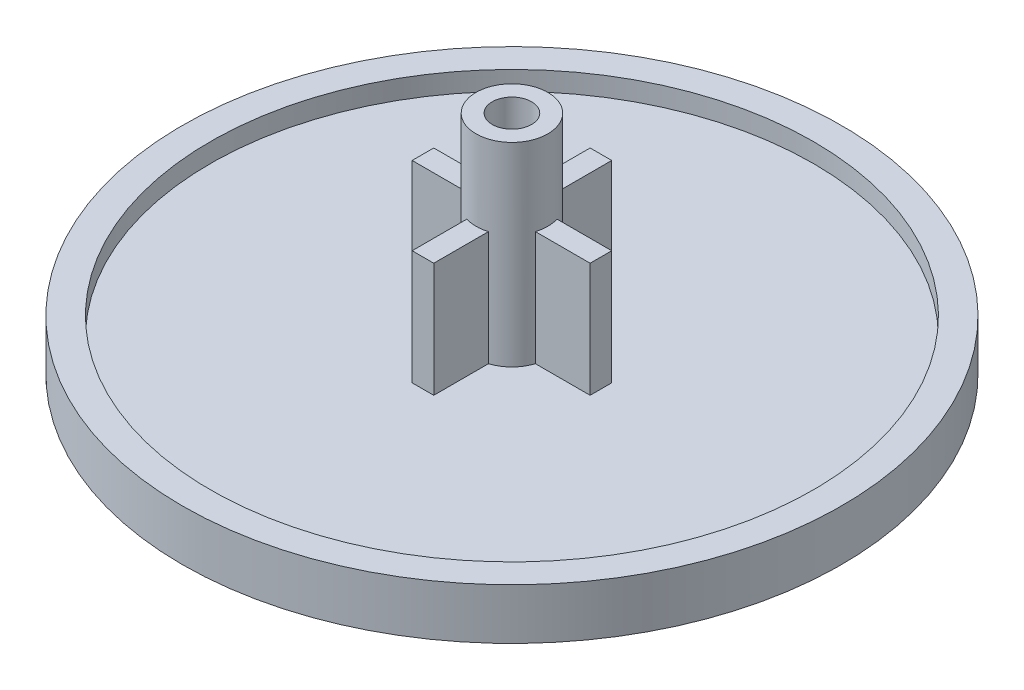
SolidWorks part; units mm, degrees
material "ABS"
ref_plane "Front Plane" through (0, 0, 0) normal (0, 0, 1) x (1, 0, 0)
ref_plane "Top Plane" through (0, 0, 0) normal (0, 1, 0) x (1, 0, 0)
ref_plane "Right Plane" through (0, 0, 0) normal (1, 0, 0) x (0, 0, -1)
sketch "Sketch1" plane through (0, 0, 0) normal (0, 1, 0) x (1, 0, 0)
  circle A0 centre (0, 0) radius 13.1699
  dimension "D1" = 26.3398
extrude "Boss-Extrude1" add sketch "Sketch1" along normal blind 1.27
sketch "Sketch2" plane through (0, 1.27, 0) normal (0, 1, 0) x (1, 0, 0)
  circle A0 centre (0, 0) radius 12.0523
  circle A1 centre (0, 0) radius 13.1699 construction
  circle A3 centre (0, 0) radius 13.1699
  circle A4 centre (0, 0) radius 13.1699
  dimension "D1" = 1.1176
  dimension "D2" = 0
extrude "Boss-Extrude2" add sketch "Sketch2" along normal blind 0.762
sketch "Sketch3" plane through (0, 1.27, 0) normal (0, 1, 0) x (1, 0, 0)
  circle A0 centre (0, 0) radius 1.4351
  dimension "D1" = 2.8702
extrude "Boss-Extrude3" add sketch "Sketch3" along normal blind 7.7724
sketch "Sketch6" plane through (0, 0, 0) normal (0, 0, 1) x (1, 0, 0)
  line L0 (13.1699, 2.032) -> (-13.1699, 2.032) construction
  line L1 (-3.556, 0) -> (3.556, 0)
  line L2 (-3.556, 0) -> (-3.556, 5.842)
  line L3 (-3.556, 5.842) -> (3.556, 5.842)
  line L4 (3.556, 0) -> (3.556, 5.842)
  line L5 (-3.556, 0) -> (3.556, 5.842) construction
  line L6 (-3.556, 5.842) -> (3.556, 0) construction
  line L7 (-13.1699, 0) -> (13.1699, 0) construction
  point P4 (0, 2.921)
  dimension "D1" = 7.112
  dimension "D2" = 3.81
extrude "Boss-Extrude4" add sketch "Sketch6" along normal mid plane 0.8636
sketch "Sketch7" plane through (0, 0, 0) normal (1, 0, 0) x (0, 0, -1)
  line L0 (-13.1699, 0) -> (13.1699, 0) construction
  line L1 (-3.556, 0) -> (3.556, 0)
  line L2 (-3.556, 0) -> (-3.556, 5.842)
  line L3 (-3.556, 5.842) -> (3.556, 5.842)
  line L4 (3.556, 0) -> (3.556, 5.842)
  line L5 (-3.556, 0) -> (3.556, 5.842) construction
  line L6 (-3.556, 5.842) -> (3.556, 0) construction
  line L7 (-0.4318, 5.842) -> (0.4318, 5.842) construction
  point P4 (0, 2.921)
  dimension "D1" = 7.112
extrude "Boss-Extrude5" add sketch "Sketch7" along normal mid plane 0.8636
sketch "Sketch4" plane through (0, 9.0424, 0) normal (0, 1, 0) x (1, 0, 0)
  circle A0 centre (0, 0) radius 0.7874
  dimension "D1" = 1.5748
extrude "Cut-Extrude1" cut sketch "Sketch4" against normal up to surface (7.7724 mm away) up to face at (0, 1.27, 12.0523)
